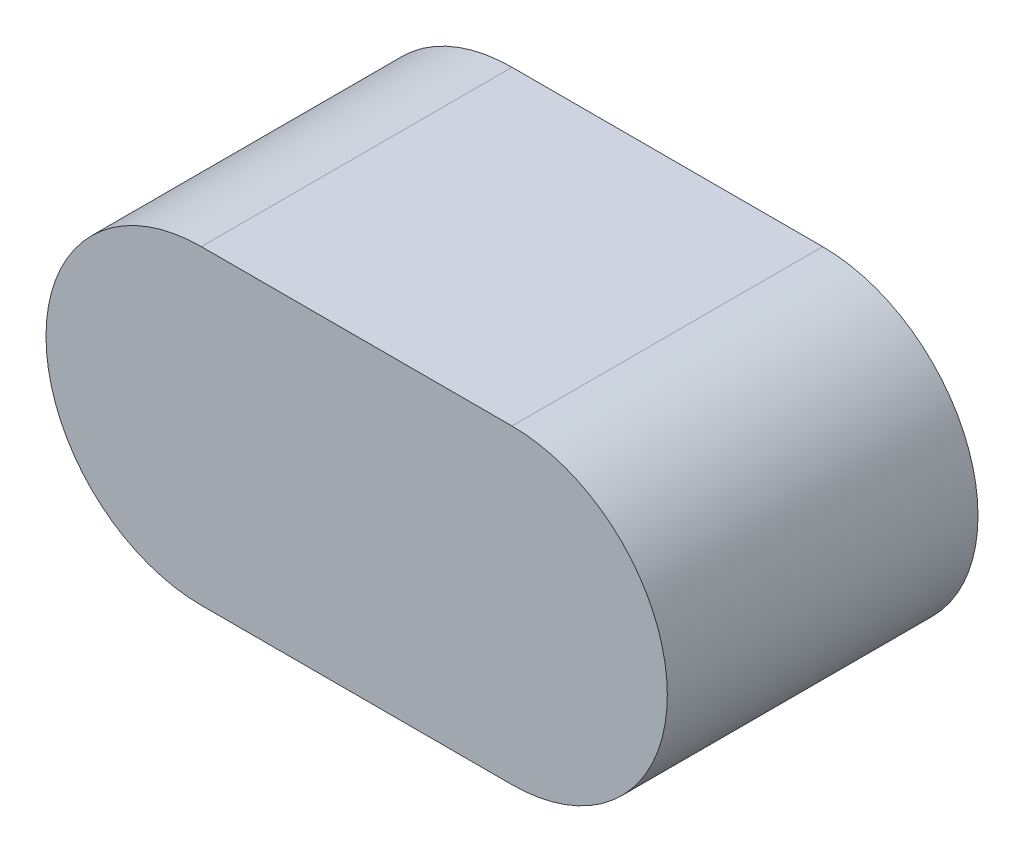
SolidWorks part; units mm, degrees
ref_plane "前视基准面" through (0, 0, 0) normal (0, 0, 1) x (1, 0, 0)
ref_plane "上视基准面" through (0, 0, 0) normal (0, 1, 0) x (1, 0, 0)
ref_plane "右视基准面" through (0, 0, 0) normal (1, 0, 0) x (0, 0, -1)
other "Configuration Table"
sketch "草图1" plane through (0, 0, 0) normal (0, 0, 1) x (1, 0, 0)
  line L0 (-4.1429, 2.1905) -> (-1.1429, 2.1905) construction
  line L1 (-4.1429, 3.6905) -> (-1.1429, 3.6905)
  line L2 (-4.1429, 0.6905) -> (-1.1429, 0.6905)
  arc A0 (-4.1429, 3.6905) -> (-4.1429, 0.6905) centre (-4.1429, 2.1905) ccw
  arc A1 (-1.1429, 0.6905) -> (-1.1429, 3.6905) centre (-1.1429, 2.1905) ccw
  point P2 (-2.6429, 2.1905)
  dimension "D1" = 1.5
  dimension "D2" = 3
extrude "凸台-拉伸1" add sketch "草图1" along normal blind 3
